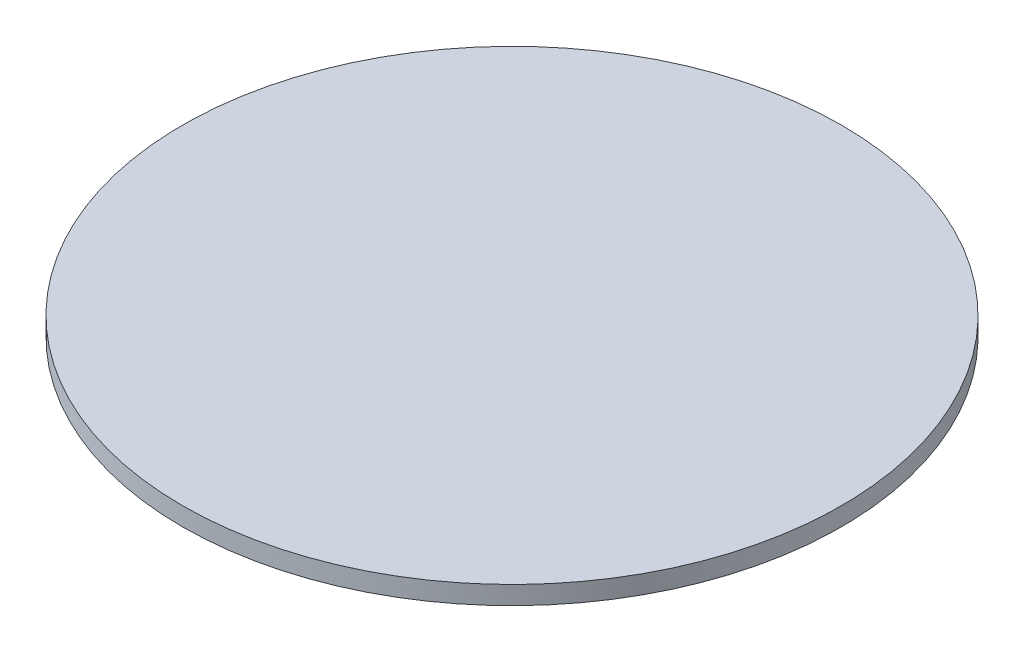
SolidWorks part; units mm, degrees
material "ABS"
ref_plane "前视基准面" through (0, 0, 0) normal (0, 0, 1) x (1, 0, 0)
ref_plane "上视基准面" through (0, 0, 0) normal (0, 1, 0) x (1, 0, 0)
ref_plane "右视基准面" through (0, 0, 0) normal (1, 0, 0) x (0, 0, -1)
other "Configuration Table"
sketch "草图1" plane through (0, 0, 0) normal (0, 1, 0) x (1, 0, 0)
  circle A0 centre (0, 0) radius 17.95
  dimension "D1" = 35.9
extrude "凸台-拉伸1" add sketch "草图1" along normal blind 1
